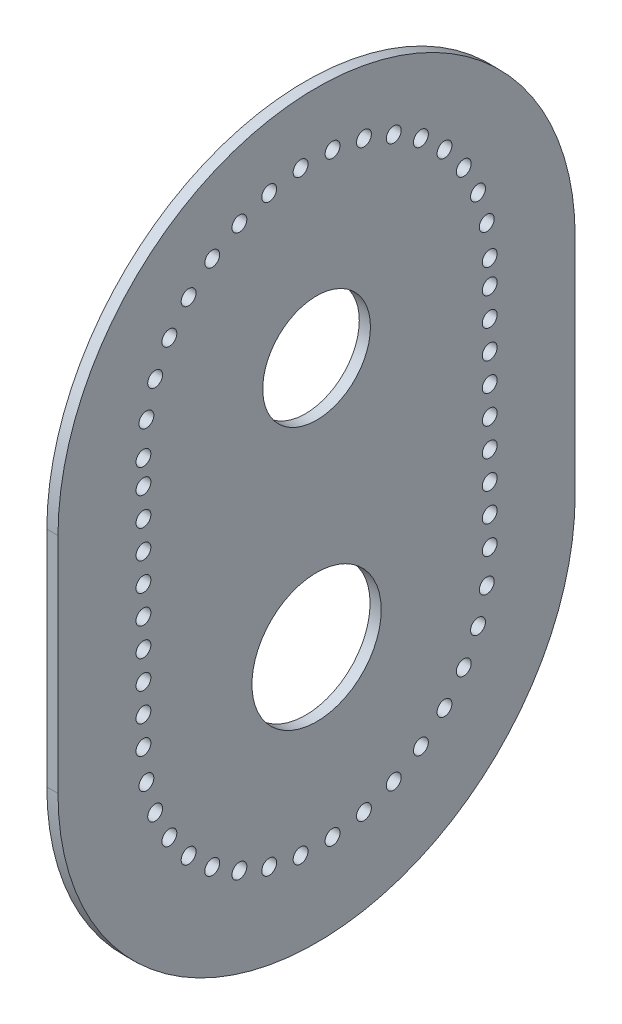
SolidWorks part; units mm, degrees
ref_plane "Front Plane" through (0, 0, 0) normal (0, 0, 1) x (1, 0, 0)
ref_plane "Top Plane" through (0, 0, 0) normal (0, 1, 0) x (1, 0, 0)
ref_plane "Right Plane" through (0, 0, 0) normal (1, 0, 0) x (0, 0, -1)
sketch "Sketch1" plane through (0, 0, 0) normal (1, 0, 0) x (0, 0, -1)
  line L4 (0, 50.1) -> (0, -50.1) construction
  line L5 (116, 50.1) -> (116, -50.1)
  line L6 (-116, 50.1) -> (-116, -50.1)
  line L10 (0, -50.1) -> (0, -51.2443)
  circle A0 centre (0, 61.0772) radius 24.1613
  circle A1 centre (0, -51.2443) radius 28.9935
  arc A4 (116, 50.1) -> (-116, 50.1) centre (0, 50.1) ccw
  arc A5 (-116, -50.1) -> (116, -50.1) centre (0, -50.1) ccw
  point P11 (0, 0)
  point P16 (0, -166.1)
  point P17 (0, 166.1)
  dimension "D6" = 48.3225
  dimension "D8" = 57.987
  dimension "D2" = 57.987
  dimension "D1" = 112.3215
  dimension "D10" = 232
  dimension "D11" = 332.2
extrude "Boss-Extrude1" add sketch "Sketch1" along normal blind 5
scale "Scale1" scale about centroid uniform scaling yes scale factor 1.5
sketch "Sketch2" plane through (6.25, 0, 0) normal (1, 0, 0) x (0, 0, -1)
  line L1 (116.5, 91.4248) -> (116.5, -77.0575) construction
  line L2 (-116.5, 91.4248) -> (-116.5, -77.0575) construction
  arc A0 (116.5, 91.4248) -> (-116.5, 91.4248) centre (0, 91.4248) ccw construction
  arc A1 (-116.5, -77.0575) -> (116.5, -77.0575) centre (0, -77.0575) ccw construction
  circle A2 centre (-116.5, -77.0575) radius 5
  circle A3 centre (116.5, -77.0575) radius 5
  circle A4 centre (-116.5, -58.0575) radius 5
  circle A5 centre (-116.5, -39.0575) radius 5
  circle A6 centre (-116.5, -20.0575) radius 5
  circle A7 centre (-116.5, -1.0575) radius 5
  circle A8 centre (-116.5, 17.9425) radius 5
  circle A9 centre (-116.5, 36.9425) radius 5
  circle A10 centre (-116.5, 55.9425) radius 5
  circle A11 centre (-116.5, 74.9425) radius 5
  circle A12 centre (116.5, -58.0575) radius 5
  circle A13 centre (116.5, -39.0575) radius 5
  circle A14 centre (116.5, -20.0575) radius 5
  circle A15 centre (116.5, -1.0575) radius 5
  circle A16 centre (116.5, 17.9425) radius 5
  circle A17 centre (116.5, 36.9425) radius 5
  circle A18 centre (116.5, 55.9425) radius 5
  circle A19 centre (116.5, 74.9425) radius 5
  circle A20 centre (-116.5, 91.4248) radius 5
  circle A21 centre (116.5, 91.4248) radius 5
  circle A24 centre (-114.5164, 112.8316) radius 5
  circle A25 centre (-108.633, 133.5094) radius 5
  circle A26 centre (-99.0503, 152.7541) radius 5
  circle A27 centre (-86.0945, 169.9103) radius 5
  circle A28 centre (-70.2069, 184.3938) radius 5
  circle A29 centre (-51.9285, 195.7113) radius 5
  circle A30 centre (-31.8817, 203.4775) radius 5
  circle A31 centre (-10.7493, 207.4278) radius 5
  circle A32 centre (10.7493, 207.4278) radius 5
  circle A33 centre (31.8817, 203.4775) radius 5
  circle A34 centre (51.9285, 195.7113) radius 5
  circle A35 centre (70.2069, 184.3938) radius 5
  circle A36 centre (86.0945, 169.9103) radius 5
  circle A37 centre (99.0503, 152.7541) radius 5
  circle A38 centre (108.633, 133.5094) radius 5
  circle A39 centre (114.5164, 112.8316) radius 5
  circle A40 centre (116.5, 91.4248) radius 5
  circle A41 centre (-114.5164, -98.4643) radius 5
  circle A42 centre (-108.633, -119.1421) radius 5
  circle A43 centre (-99.0503, -138.3868) radius 5
  circle A44 centre (-86.0945, -155.543) radius 5
  circle A45 centre (-70.2069, -170.0265) radius 5
  circle A46 centre (-51.9285, -181.344) radius 5
  circle A47 centre (-31.8817, -189.1102) radius 5
  circle A48 centre (-10.7493, -193.0605) radius 5
  circle A49 centre (10.7493, -193.0605) radius 5
  circle A50 centre (31.8817, -189.1102) radius 5
  circle A51 centre (51.9285, -181.344) radius 5
  circle A52 centre (70.2069, -170.0265) radius 5
  circle A53 centre (86.0945, -155.543) radius 5
  circle A54 centre (99.0503, -138.3868) radius 5
  circle A55 centre (108.633, -119.1421) radius 5
  circle A56 centre (114.5164, -98.4643) radius 5
  circle A57 centre (116.5, -77.0575) radius 5
  point P4 (0, 7.1837)
  point P49 (0, 0)
  point P51 (0, 0)
  point P52 (0, 0)
  point P92 (0, 91.4248)
  point P127 (0, -77.0575)
  dimension "D1" = 116.5
  dimension "D2" = 10
  dimension "D3" = 10
  dimension "D6" = 10
  dimension "D7" = 10
  dimension "D4" = 9
  dimension "D5" = 9
  dimension "D8" = 18
  dimension "D9" = 18
extrude "Cut-Extrude1" cut sketch "Sketch2" against normal blind 10 contours A12 | A3 | A56 | A55 | A14 | A15 | A16 | A17 | A18 | A19 | A21 | A39 | A38 | A36 | A35 | A34 | A33 | A32 | A31 | A30 | A29 | A28 | A27 | A26 | A25 | A24 | A20 | A11 | A10 | A9 | A8 | A7 | A6 | A5 | A4 | A2 | A41 | A42 | A43 | A44 | A45 | A46 | A47 | A48 | A49 | A50 | A51 | A52 | A54 | A53 | A13 | A37
